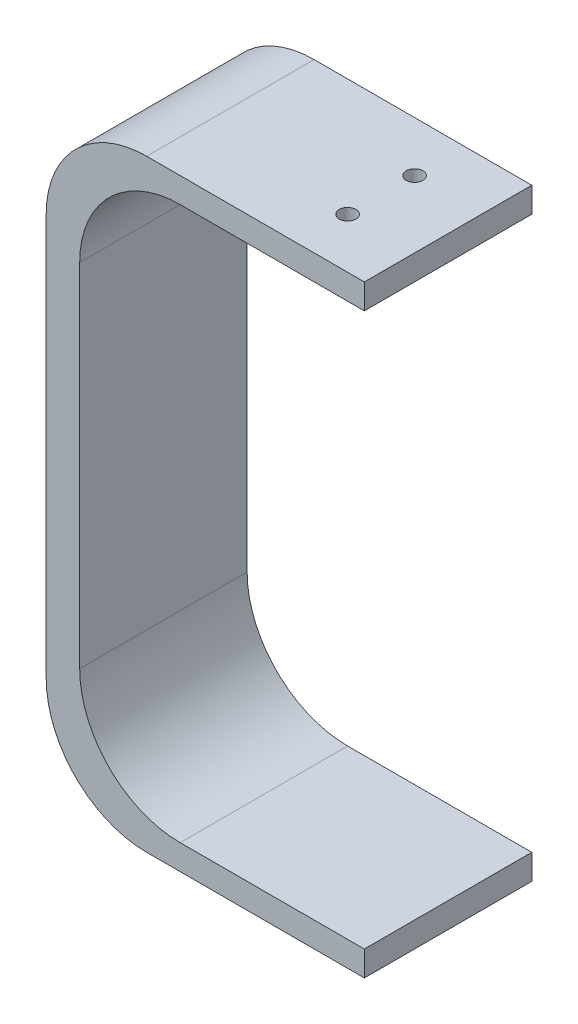
SolidWorks part; units mm, degrees
ref_plane "Front Plane" through (0, 0, 0) normal (0, 0, 1) x (1, 0, 0)
ref_plane "Top Plane" through (0, 0, 0) normal (0, 1, 0) x (1, 0, 0)
ref_plane "Right Plane" through (0, 0, 0) normal (1, 0, 0) x (0, 0, -1)
sketch "Sketch1" plane through (0, 0, 0) normal (0, 0, 1) x (1, 0, 0)
  line L2 (-20, -165) -> (0, -165)
  line L3 (0, -165) -> (0, -172.5)
  line L4 (0, -172.5) -> (-51.3765, -172.5)
  line L6 (-55, 7.5) -> (0, 7.5)
  line L7 (0, 7.5) -> (0, 0)
  line L9 (-55, 7.5) -> (-65, 7.5)
  line L10 (-20, -165) -> (-55, -165)
  line L11 (-51.3765, -172.5) -> (-65, -172.5)
  line L14 (-85, -30) -> (-85, -135)
  line L15 (-95, -22.5) -> (-95, -142.5)
  line L16 (-55, 0) -> (0, 0)
  arc A0 (-55, 0) -> (-85, -30) centre (-55, -30) ccw
  arc A1 (-85, -135) -> (-55, -165) centre (-55, -135) ccw
  arc A2 (-95, -22.5) -> (-65, 7.5) centre (-65, -22.5) cw
  arc A3 (-65, -172.5) -> (-95, -142.5) centre (-65, -142.5) cw
  dimension "D6" = 30
  dimension "D7" = 30
  dimension "D8" = 30
  dimension "D9" = 30
  dimension "D2" = 7.5
  dimension "D3" = 7.5
  dimension "D4" = 20
  dimension "D5" = 55
  dimension "D10" = 85
  dimension "D11" = 95
  dimension "D14" = 165
  dimension "D15" = 13.6235
extrude "Boss-Extrude1" add sketch "Sketch1" along normal blind 50
sketch "Sketch3" plane through (0, 0, 0) normal (0, -1, 0) x (1, 0, 0)
  line L0 (-65, 0) -> (0, 0) construction
  line L1 (-65, 50) -> (0, 50) construction
  line L2 (0, 50) -> (0, 0) construction
  circle A0 centre (-20, 35) radius 2.5
  circle A1 centre (-20, 15) radius 2.5
  dimension "D1" = 5
  dimension "D2" = 5
  dimension "D3" = 15
  dimension "D4" = 15
  dimension "D5" = 20
  dimension "D6" = 20
extrude "Cut-Extrude1" cut sketch "Sketch3" against normal blind 24
